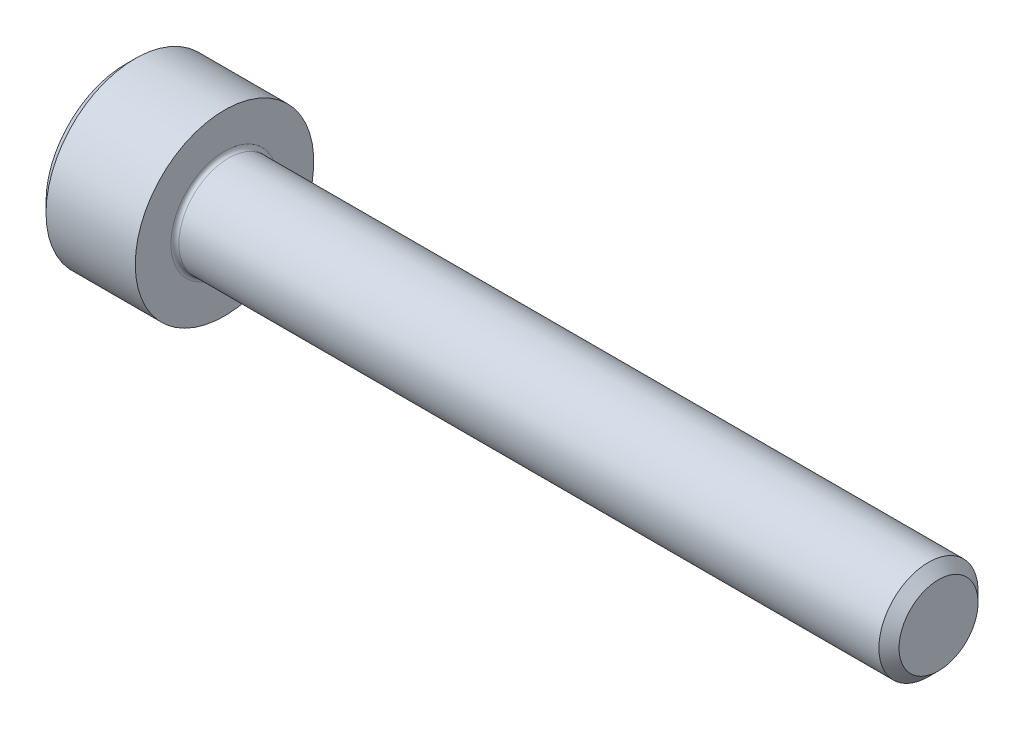
SolidWorks part; units mm, degrees
ref_plane "Plane1" through (0, 0, 0) normal (0, 0, 1) x (1, 0, 0)
ref_plane "Plane2" through (0, 0, 0) normal (0, 1, 0) x (1, 0, 0)
ref_plane "Plane3" through (0, 0, 0) normal (1, 0, 0) x (0, 0, -1)
sketch "BodySke" plane through (0, 0, 0) normal (0, 0, 1) x (1, 0, 0)
  line L0 (0, 0) -> (0, 2)
  line L1 (0.25, 2.25) -> (2.5, 2.25)
  line L2 (2.5, 2.25) -> (2.5, 1.25)
  line L3 (2.5, 1.25) -> (20.2465, 1.25)
  line L4 (20.5, 0.9965) -> (20.5, 0)
  line L5 (20.5, 0) -> (0, 0)
  line L6 (-31.75, 0) -> (127, 0) construction
  line L7 (0, 2) -> (0.25, 2.25)
  line L8 (20.5, 0.9965) -> (20.2465, 1.25)
  line L9 (0, -2) -> (0.25, -2.25) construction
  line L10 (20.5, -0.9965) -> (20.2465, -1.25) construction
  line L11 (2.95, 9.525) -> (2.95, 3.175) construction
  line L12 (2.5, 9.525) -> (2.5, -0.9965) construction
  line L13 (-31.5, 9.525) -> (-31.5, 3.175) construction
  dimension "D1" = 18
  dimension "Diameter" = 2.5
  dimension "Head_ht" = 2.5
  dimension "Body_ch_ang" = 45
  dimension "Head_dia" = 4.5
  dimension "Head_ch_ang" = 45
  dimension "Minor_dia" = 1.993
  dimension "Advance" = 0.45
  dimension "Thread_length" = 52
  dimension "Head_ch_ht" = 0.25
revolve "Base-Revolve" add sketch "BodySke" angle 360 about L6
cosmetic thread "ThreadCosmetic" [suppressed] parameters "Thread_length"=17.55, "Thread_minor"=1.993
fillet "Fillet1" radius 0.1 1 edges at (2.5, 0, 1.25)
sketch "Sketch2" plane through (0, 0, 0) normal (0, 0, 1) x (1, 0, 0)
  line L0 (0, 1.0225) -> (1.1, 1.0225)
  line L1 (1.1, 1.0225) -> (1.6903, 0)
  line L2 (-31.75, 0) -> (127, 0) construction
  line L3 (1.6903, 0) -> (0, 0)
  line L4 (0, 0) -> (0, 1.0225)
  line L5 (0, 2) -> (0, -2) construction
  line L6 (0, 0) -> (47.625, 0) construction
  line L7 (2.5, -2.25) -> (2.5, 2.25) construction
  dimension "D1" = 1.0225
  dimension "D2" = 60
  dimension "Wall_thickness" = 1.4
revolve "Hex-PreBroach" cut sketch "Sketch2" angle 360 about L6
sketch "Sketch3" plane through (0, 0, 0) normal (-1, 0, 0) x (0, 0.5, 0.866)
  line L0 (0.5903, 1.0225) -> (-0.5903, 1.0225)
  line L1 (-0.5903, 1.0225) -> (-1.1807, 0)
  line L2 (0.5903, 1.0225) -> (1.1807, 0)
  line L3 (0.5903, -1.0225) -> (1.1807, 0)
  line L4 (0.5903, -1.0225) -> (-0.5903, -1.0225)
  line L5 (-0.5903, -1.0225) -> (-1.1807, 0)
  dimension "D1" = 1.0225
  dimension "D2" = 1.0225
  dimension "Hex_size" = 2.045
extrude "Hex" cut sketch "Sketch3" against normal blind 1.1
sketch "Sketch4" plane through (0, 0, 0) normal (-1, 0, 0) x (0, 0, 1)
  line L0 (0, 0) -> (1.2446, 0)
  line L1 (0, 0) -> (6.1484, 3.5498) construction
  line L2 (0, 0) -> (0.6223, 1.0779)
  line L3 (1.0085, 0.2596) -> (1.19, 0.3644)
  line L4 (0.7291, 0.7436) -> (0.9106, 0.8484)
  arc A0 (1.0085, 0.2596) -> (0.7291, 0.7436) centre (0, 0) ccw
  arc A1 (1.2446, 0) -> (1.19, 0.3644) centre (0, 0) ccw
  arc A2 (0.6223, 1.0779) -> (0.9106, 0.8484) centre (0, 0) cw
  dimension "D1" = 30
  dimension "Spline_n_dim" = 2.0828
  dimension "Spline_m_dim" = 2.4892
  dimension "D2" = 60
  dimension "D3" = 0.2794
  dimension "Spline_p_dim" = 0.5588
extrude "Spline" [suppressed] cut sketch "Sketch4" against normal blind 1.1
pattern_circular "CirPattern1" [suppressed] count 6 over 360 about axis through (-31.75, 0, 0) along (1, 0, 0)
sketch "Sketch5" plane through (0, 0, 0) normal (0, 0, 1) x (1, 0, 0)
  line L0 (-31.75, 0) -> (127, 0) construction
  line L2 (0, 2) -> (0, -2) construction
  circle A0 centre (0.1, 0) radius 0.005
  dimension "Drilled_hole_dia" = 0.01
  dimension "Drilled_hole_loc" = 0.1
extrude "Hole" [suppressed] cut sketch "Sketch5" against normal through all and the other way through all
pattern_circular "Drilled-4" [suppressed] count 2 every 60 about axis through (-31.75, 0, 0) along (1, 0, 0)
pattern_circular "Drilled-6" [suppressed] count 3 every 60 about axis through (-31.75, 0, 0) along (1, 0, 0)
sketch "ThdSchSke" plane through (0, 0, 0) normal (0, 0, 1) x (1, 0, 0)
  line L0 (2.95, -0.9965) -> (2.7725, -1.25)
  line L1 (2.95, -0.9965) -> (3.1275, -1.25)
  line L2 (3.1275, -1.25) -> (3.1275, -1.5625)
  line L3 (-3.175, 0) -> (5.1513, 0) construction
  line L5 (3.1275, -1.5625) -> (2.7725, -1.5625)
  line L6 (2.7725, -1.5625) -> (2.7725, -1.25)
  line L7 (0, 2) -> (0, -2) construction
  dimension "Thread_minor" = 1.993
  dimension "Diameter" = 2.5
  dimension "Start" = 2.95
  dimension "SideAngle" = 55
  dimension "VeeAngle" = 70
  dimension "Overcut" = 3.125
revolve "ThreadSchematic" [suppressed] cut sketch "ThdSchSke" angle 360 about L3
pattern_linear "ThdSchPat" [suppressed]
equation "\"D2@Sketch3\" = \"Hex_size@Sketch3\" / 2"
equation "\"D1@Sketch3\" = \"Hex_size@Sketch3\" / 2"
equation "\"D1@Sketch2\" = \"Hex_size@Sketch3\" / 2"
equation "\"D3@Sketch4\" = \"Spline_p_dim@Sketch4\" / 2"
equation "\"Thread_minor@ThreadCosmetic\"  =  \"Minor_dia@BodySke\""
equation "\"D2@CirPattern1\" = 360 / \"Num_teeth@CirPattern1\""
equation "\"Wall_thickness@Sketch2\" = \"Head_ht@BodySke\" - \"Key_eng@Hex\""
equation "\"Thread_length@ThreadCosmetic\" = 17.55"
equation "\"Thread_minor@ThdSchSke\" = \"Minor_dia@BodySke\""
equation "\"Diameter@ThdSchSke\" = \"Diameter@BodySke\""
equation "\"Overcut@ThdSchSke\" = \"Diameter@BodySke\" * 1.25"
equation "\"Start@ThdSchSke\"= \"Head_ht@BodySke\" + 18 - \"Thread_length@ThreadCosmetic\" '---Non-countersunk---"
equation "\"Num_threads@ThdSchPat\" = int( \"Thread_length@ThreadCosmetic\" / \"Advance@BodySke\" + 0.999 )  + 1"
equation "\"Advance@ThdSchPat\" = \"Thread_length@ThreadCosmetic\" /  (\"Num_threads@ThdSchPat\" - 1) 'relax it"
equation "\"Num_threads@ThdSchPat\" = \"Num_threads@ThdSchPat\" - sgn( \"Num_threads@ThdSchPat\" - 1) '---chamfered tips only---"
